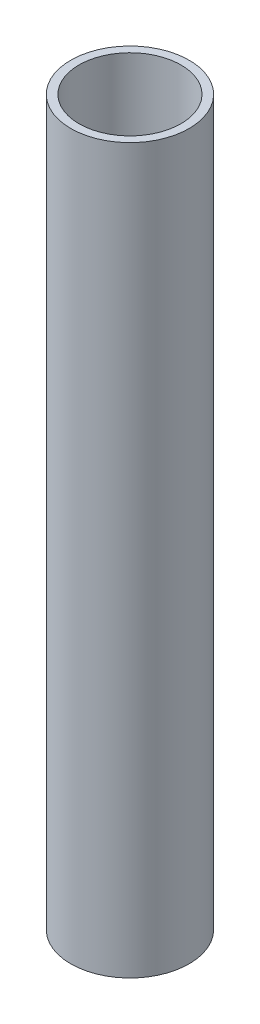
SolidWorks part; units mm, degrees
ref_plane "Front Plane" through (0, 0, 0) normal (0, 0, 1) x (1, 0, 0)
ref_plane "Top Plane" through (0, 0, 0) normal (0, 1, 0) x (1, 0, 0)
ref_plane "Right Plane" through (0, 0, 0) normal (1, 0, 0) x (0, 0, -1)
sketch "Sketch1" plane through (0, 0, 0) normal (0, 1, 0) x (1, 0, 0)
  circle A0 centre (0, 0) radius 7.75
  circle A1 centre (0, 0) radius 9
  dimension "D1" = 18
  dimension "D2" = 15.5
extrude "Boss-Extrude1" add sketch "Sketch1" along normal blind 110
